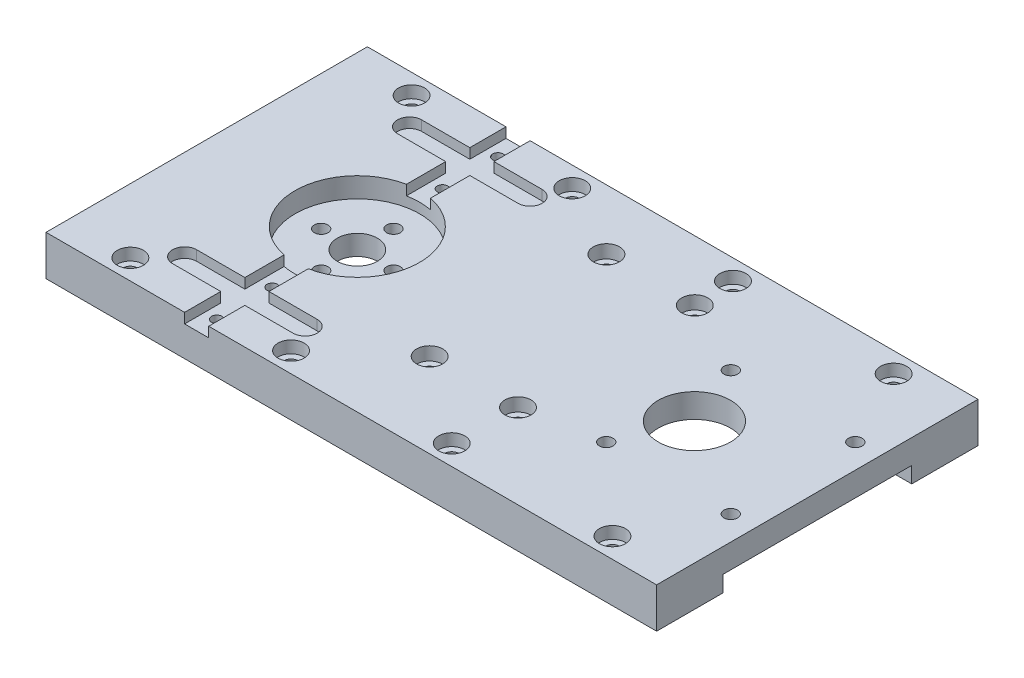
SolidWorks part; units mm, degrees
ref_plane "Front Plane" through (0, 0, 0) normal (0, 0, 1) x (1, 0, 0)
ref_plane "Top Plane" through (0, 0, 0) normal (0, 1, 0) x (1, 0, 0)
ref_plane "Right Plane" through (0, 0, 0) normal (1, 0, 0) x (0, 0, -1)
sketch "Sketch1" plane through (0, 0, 0) normal (0, 1, 0) x (1, 0, 0)
  line L1 (0, 0) -> (152, 0)
  line L2 (0, 0) -> (0, 80)
  line L3 (0, 80) -> (152, 80)
  line L4 (152, 0) -> (152, 80)
  line L5 (0, 0) -> (152, 80) construction
  line L6 (0, 80) -> (152, 0) construction
  point P5 (72.98, 45.6883)
  dimension "D1" = 152
  dimension "D2" = 80
extrude "Boss-Extrude1" add sketch "Sketch1" along normal blind 10
sketch "Sketch2" plane through (0, 10, 0) normal (0, 1, 0) x (1, 0, 0)
  circle A0 centre (37.5, 40) radius 15.5
extrude "Cut-Extrude1" cut sketch "Sketch2" against normal blind 5
sketch "Sketch3" plane through (0, 5, 0) normal (0, 1, 0) x (1, 0, 0)
  circle A0 centre (37.5, 40) radius 5
extrude "Cut-Extrude2" cut sketch "Sketch3" against normal blind 5
sketch "Sketch4" plane through (0, 10, 0) normal (0, 1, 0) x (1, 0, 0)
  line L0 (34.5, 24.7931) -> (34.5, 15)
  line L3 (34.5, 0) -> (40.5, 0)
  line L5 (40.5, 15) -> (52.5, 15)
  line L6 (22.5, 9) -> (34.5, 9)
  line L7 (40.5, 24.7931) -> (40.5, 15)
  line L9 (22.5, 15) -> (34.5, 15)
  line L13 (34.5, 9) -> (34.5, 0)
  line L14 (40.5, 9) -> (52.5, 9)
  line L15 (40.5, 9) -> (40.5, 0)
  arc A1 (34.5, 24.7931) -> (40.5, 24.7931) centre (37.5, 40) ccw
  arc A2 (22.5, 15) -> (22.5, 9) centre (22.5, 12) ccw
  arc A3 (52.5, 9) -> (52.5, 15) centre (52.5, 12) ccw
  point P10 (37.5, 12)
extrude "Cut-Extrude3" cut sketch "Sketch4" against normal blind 2.5
pattern_circular "CirPattern1" count 2 over 360 about axis through (37.5, 0, -40) along (0, 1, 0) of "Cut-Extrude3"
sketch "Sketch5" plane through (0, 10, 0) normal (0, 1, 0) x (1, 0, 0)
  line L0 (0, 80) -> (0, 0) construction
  line L1 (152, 0) -> (152, 80) construction
  circle A0 centre (121.41, 40) radius 9
  dimension "D1" = 152
extrude "Cut-Extrude4" cut sketch "Sketch5" against normal blind 6 contours A0
sketch "Sketch6" plane through (0, 4, 0) normal (0, 1, 0) x (1, 0, 0)
  line L1 (105, 16.5) -> (152, 16.5)
  line L2 (105, 16.5) -> (105, 63.5)
  line L3 (105, 63.5) -> (152, 63.5)
  line L4 (152, 16.5) -> (152, 63.5)
  line L5 (105, 16.5) -> (152, 63.5) construction
  line L6 (105, 63.5) -> (152, 16.5) construction
  point P4 (131.2584, 36.4298)
extrude "Cut-Extrude5" cut sketch "Sketch6" against normal blind 4
fillet "Fillet1" radius 3 2 edges at (105, 2, -63.5) (105, 2, -16.5)
sketch "Sketch13" plane through (0, 10, 0) normal (0, 1, 0) x (1, 0, 0)
  point P13 (114.96, 55.5)
  point P15 (145.96, 55.5)
  point P17 (114.96, 24.5)
  point P19 (145.96, 24.5)
sketch "Sketch7" plane through (0, 10, 0) normal (0, 1, 0) x (1, 0, 0)
  point P0 (16, 75)
  point P4 (56, 75)
  point P19 (16, 5)
  point P21 (56, 5)
  point P38 (96, 75)
  point P40 (96, 5)
  point P42 (136, 5)
  point P62 (136, 75)
hole_wizard "CBORE for M3 Pan Head Screw1" positions "Sketch7" profile "Sketch8" counterbore size "M3" standard "JIS" end condition through all
sketch "Sketch8" plane through (16, 10, -75) normal (1, 0, 0) x (0, 0, 1)
  line L0 (0, 0) -> (0, 10)
  line L1 (0, 10) -> (1.7, 10)
  line L3 (1.7, 10) -> (1.7, 3)
  line L4 (1.7, 3) -> (3.25, 3)
  line L5 (3.25, 3) -> (3.25, 0)
  line L7 (3.25, 0) -> (0, 0)
  line L11 (0, -6.35) -> (0, 107.95) construction
  dimension "Thru Hole Dia." = 3.4
  dimension "Thru Hole Depth" = 10
  dimension "C'Bore Dia." = 6.5
  dimension "C'Bore Depth" = 3
sketch "Sketch9" plane through (0, 10, 0) normal (0, 1, 0) x (1, 0, 0)
  point P0 (96.5, 65)
  point P2 (96.5, 21)
  point P4 (74.5, 21)
  point P6 (74.5, 65)
hole_wizard "CBORE for M3 Pan Head Screw2" positions "Sketch9" profile "Sketch10" counterbore size "M3" standard "JIS" end condition through all
sketch "Sketch10" plane through (96.5, 10, -65) normal (1, 0, 0) x (0, 0, 1)
  line L0 (0, 0) -> (0, 10)
  line L1 (0, 10) -> (1.7, 10)
  line L3 (1.7, 10) -> (1.7, 3.3)
  line L4 (1.7, 3.3) -> (3.25, 3.3)
  line L5 (3.25, 3.3) -> (3.25, 0)
  line L7 (3.25, 0) -> (0, 0)
  line L11 (0, -6.35) -> (0, 107.95) construction
  dimension "Thru Hole Dia." = 3.4
  dimension "Thru Hole Depth" = 10
  dimension "C'Bore Dia." = 6.5
  dimension "C'Bore Depth" = 3.3
sketch "Sketch11" plane through (0, 7.5, 0) normal (0, 1, 0) x (1, 0, 0)
  point P0 (37.5, 75)
  point P2 (37.5, 61.2)
  point P4 (37.5, 18.8)
  point P6 (37.5, 5)
hole_wizard "Tap Drill for M3x0.5 Tap1" positions "Sketch11" profile "Sketch12" hole size "M3x0.5" standard "JIS" end condition through all
sketch "Sketch12" plane through (37.5, 7.5, -75) normal (1, 0, 0) x (0, 0, 1)
  line L0 (0, 0) -> (0, 7.5)
  line L1 (0, 7.5) -> (1.3, 7.5)
  line L2 (1.3, 7.5) -> (1.3, 0)
  line L5 (1.3, 0) -> (0, 0)
  line L11 (0, -6.35) -> (0, 107.95) construction
  dimension "Thru Hole Dia." = 2.6
  dimension "Thru Hole Depth" = 7.5
hole_wizard "Tap Drill for M3x0.5 Tap2" positions "Sketch13" profile "Sketch14" hole size "M3x0.5" standard "JIS" end condition through all
sketch "Sketch14" plane through (114.96, 10, -55.5) normal (1, 0, 0) x (0, 0, 1)
  line L0 (0, 0) -> (0, 10)
  line L1 (0, 10) -> (1.7, 10)
  line L2 (1.7, 10) -> (1.7, 0)
  line L5 (1.7, 0) -> (0, 0)
  line L11 (0, -6.35) -> (0, 107.95) construction
  dimension "Thru Hole Dia." = 3.4
  dimension "Thru Hole Depth" = 10
sketch "Sketch15" plane through (0, 5, 0) normal (0, 1, 0) x (1, 0, 0)
  point P0 (37.5, 49)
  point P2 (46.5, 40)
  point P4 (28.5, 40)
  point P6 (37.5, 31)
hole_wizard "Tap Drill for M3x0.5 Tap3" positions "Sketch15" profile "Sketch16" hole size "M3x0.5" standard "JIS" end condition through all
sketch "Sketch16" plane through (37.5, 5, -49) normal (1, 0, 0) x (0, 0, 1)
  line L0 (0, 0) -> (0, 5)
  line L1 (0, 5) -> (1.7, 5)
  line L2 (1.7, 5) -> (1.7, 0)
  line L5 (1.7, 0) -> (0, 0)
  line L11 (0, -6.35) -> (0, 107.95) construction
  dimension "Thru Hole Dia." = 3.4
  dimension "Thru Hole Depth" = 5
